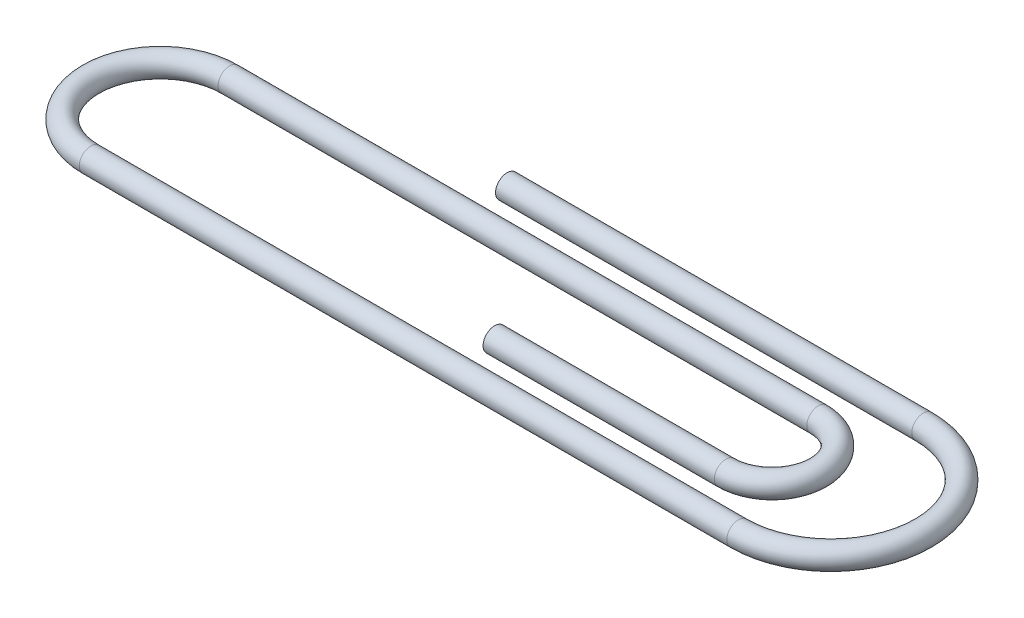
SolidWorks part; units mm, degrees
ref_plane "Front Plane" through (0, 0, 0) normal (0, 0, 1) x (1, 0, 0)
ref_plane "Top Plane" through (0, 0, 0) normal (0, 1, 0) x (1, 0, 0)
ref_plane "Right Plane" through (0, 0, 0) normal (1, 0, 0) x (0, 0, -1)
sketch "Sketch1" plane through (0, 0, 0) normal (0, 1, 0) x (1, 0, 0)
  line L0 (0, 0) -> (18, 0)
  line L2 (18, -8) -> (-10, -8)
  line L4 (-10, -2) -> (15.4603, -2)
  line L6 (15.4603, -6) -> (5.4603, -6)
  arc A0 (18, 0) -> (18, -8) centre (18, -4) cw
  arc A1 (-10, -2) -> (-10, -8) centre (-10, -5) ccw
  arc A2 (15.4603, -2) -> (15.4603, -6) centre (15.4603, -4) cw
  point P12 (22, -4)
  dimension "D5" = 4
  dimension "D6" = 3
  dimension "D7" = 2
  dimension "D1" = 10
  dimension "D2" = 32
  dimension "D3" = 10
  dimension "D4" = 5.4603
sweep "Sweep4" add path "Sketch1" circular profile diameter 1 parameters "D3"=1
